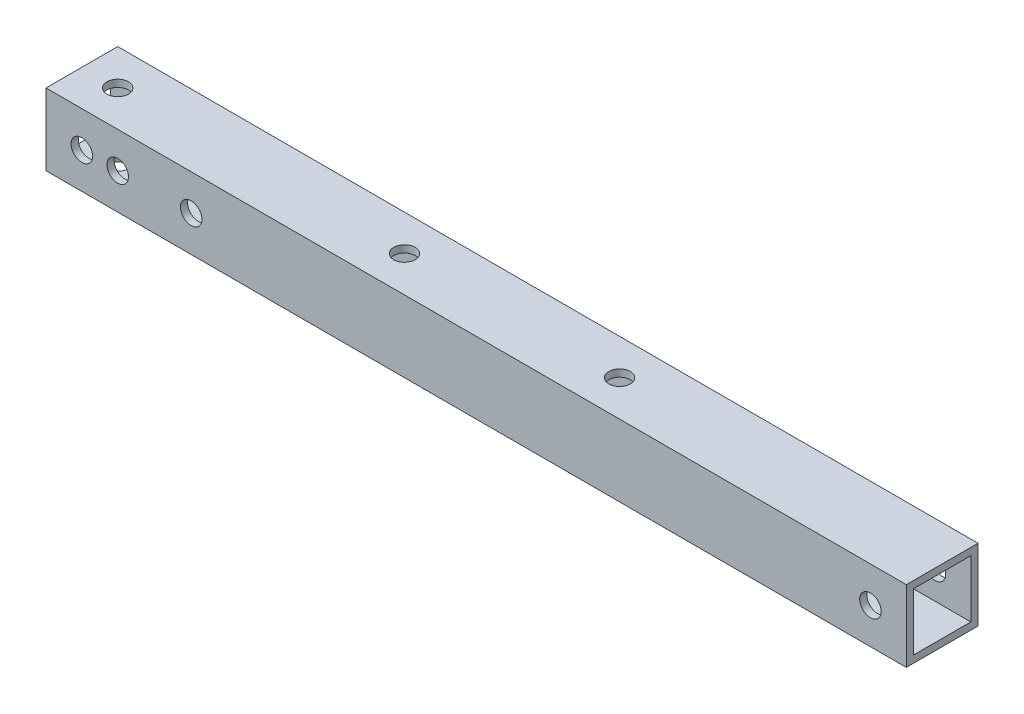
SolidWorks part; units mm, degrees
material "1060 合金"
ref_plane "正面" through (0, 0, 0) normal (0, 0, 1) x (1, 0, 0)
ref_plane "平面" through (0, 0, 0) normal (0, 1, 0) x (1, 0, 0)
ref_plane "右側面" through (0, 0, 0) normal (1, 0, 0) x (0, 0, -1)
sketch "ｽｹｯﾁ1" plane through (0, 0, 0) normal (1, 0, 0) x (0, 0, -1)
  line L1 (-5, -5) -> (5, -5)
  line L2 (-5, -5) -> (-5, 5)
  line L3 (-5, 5) -> (5, 5)
  line L4 (5, -5) -> (5, 5)
  line L5 (-5, -5) -> (5, 5) construction
  line L6 (-5, 5) -> (5, -5) construction
  point P0 (0, 0)
  dimension "D1" = 10
extrude "押し出し-薄板1" add sketch "ｽｹｯﾁ1" along normal blind 120 thin thin type one direction reverse wall 1
sketch "ｽｹｯﾁ3" plane through (0, 0, 5) normal (0, 0, 1) x (1, 0, 0)
  line L0 (0, 0) -> (120, 0) construction
  line L1 (120, 5) -> (120, -5) construction
  line L2 (0, 5) -> (0, -5) construction
  circle A0 centre (115, 0) radius 1.5
  circle A1 centre (10, 0) radius 1.5
  circle A2 centre (20.25, 0) radius 1.5
  circle A3 centre (5, 0) radius 1.5
  dimension "D2" = 3
  dimension "D3" = 10
  dimension "D4" = 10.25
  dimension "D5" = 5
  dimension "D1" = 5
extrude "ｶｯﾄ - 押し出し1" cut sketch "ｽｹｯﾁ3" against normal through all
sketch "ｽｹｯﾁ4" plane through (0, 5, 0) normal (0, 1, 0) x (1, 0, 0)
  line L0 (0, 0) -> (120, 0) construction
  line L1 (120, 5) -> (120, -5) construction
  line L2 (0, 5) -> (0, -5) construction
  line L3 (60, 5) -> (60, -5) construction
  line L4 (120, 5) -> (0, 5) construction
  line L5 (120, -5) -> (0, -5) construction
  circle A0 centre (5, 0) radius 1.5
  circle A1 centre (45, 0) radius 1.5
  circle A2 centre (75, 0) radius 1.5
  dimension "D1" = 5
  dimension "D2" = 3
  dimension "D3" = 30
  dimension "D4" = 3
extrude "ｶｯﾄ - 押し出し2" cut sketch "ｽｹｯﾁ4" against normal through all
